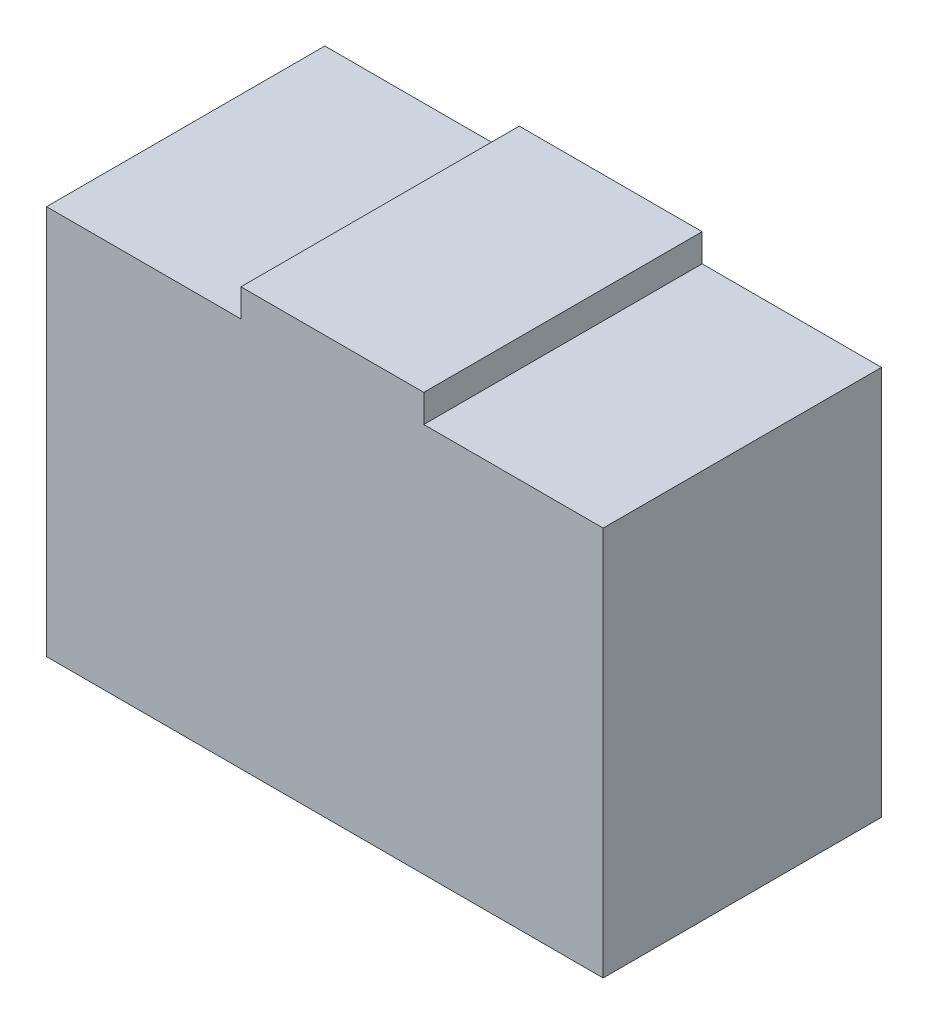
SolidWorks part; units mm, degrees
material "硅"
ref_plane "前视基准面" through (0, 0, 0) normal (0, 0, 1) x (1, 0, 0)
ref_plane "上视基准面" through (0, 0, 0) normal (0, 1, 0) x (1, 0, 0)
ref_plane "右视基准面" through (0, 0, 0) normal (1, 0, 0) x (0, 0, -1)
sketch "草图1" plane through (0, 0, 0) normal (0, 0, 1) x (1, 0, 0)
  line L1 (-0.9643, 1.0045) -> (0.0357, 1.0045)
  line L2 (-0.9643, 1.0045) -> (-0.9643, 0.3045)
  line L3 (-0.9643, 0.3045) -> (0.0357, 0.3045)
  line L4 (0.0357, 1.0045) -> (0.0357, 0.3045)
  dimension "D1" = 1
  dimension "D2" = 0.7
extrude "凸台-拉伸1" add sketch "草图1" along normal blind 0.5
sketch "草图4" plane through (0, 1.0045, 0) normal (0, 1, 0) x (1, 0, 0)
  line L0 (0.0357, 0) -> (-0.9643, 0) construction
  line L1 (-0.615, 0) -> (-0.2865, 0)
  line L2 (-0.615, 0) -> (-0.615, -0.5)
  line L3 (-0.615, -0.5) -> (-0.2865, -0.5)
  line L4 (-0.2865, 0) -> (-0.2865, -0.5)
  line L5 (0.0357, -0.5) -> (-0.9643, -0.5) construction
extrude "凸台-拉伸2" add sketch "草图4" along normal blind 0.05
